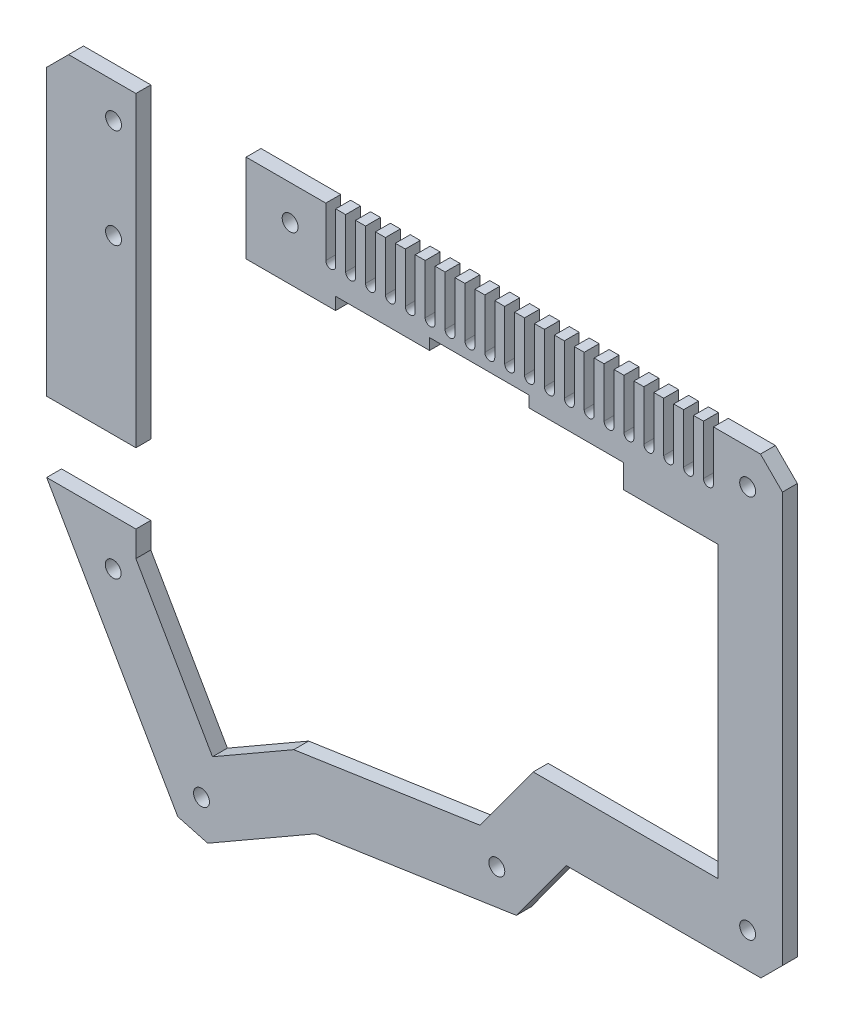
SolidWorks part; units mm, degrees
ref_plane "Plan de face" through (0, 0, 0) normal (0, 0, 1) x (1, 0, 0)
ref_plane "Plan de dessus" through (0, 0, 0) normal (0, 1, 0) x (1, 0, 0)
ref_plane "Plan de droite" through (0, 0, 0) normal (1, 0, 0) x (0, 0, -1)
sketch "Esquisse1" plane through (0, 0, 0) normal (0, 0, 1) x (1, 0, 0)
  line L0 (-117.3419, -15.4198) -> (-103.3409, -15.4198) construction
  line L1 (-103.3409, -15.4198) -> (-103.3409, -29.4208) construction
  line L2 (-103.3409, -29.4208) -> (-117.3419, -29.4208) construction
  line L3 (-117.3419, -29.4208) -> (-117.3419, -15.4198) construction
  line L4 (-98.3406, -27.0457) -> (-98.3406, -13.0447) construction
  line L5 (-98.3406, -13.0447) -> (-84.3396, -13.0447) construction
  line L6 (-84.3396, -13.0447) -> (-84.3396, -27.0457) construction
  line L7 (-84.3396, -27.0457) -> (-98.3406, -27.0457) construction
  line L8 (-79.3392, -24.6705) -> (-79.3392, -10.6695) construction
  line L9 (-79.3392, -10.6695) -> (-65.3382, -10.6695) construction
  line L10 (-65.3382, -10.6695) -> (-65.3382, -24.6705) construction
  line L11 (-65.3382, -24.6705) -> (-79.3392, -24.6705) construction
  line L12 (-60.3379, -27.0457) -> (-60.3379, -13.0447) construction
  line L13 (-60.3379, -13.0447) -> (-46.3369, -13.0447) construction
  line L14 (-46.3369, -13.0447) -> (-46.3369, -27.0457) construction
  line L15 (-46.3369, -27.0457) -> (-60.3379, -27.0457) construction
  line L16 (-41.3365, -31.796) -> (-41.3365, -17.795) construction
  line L17 (-41.3365, -17.795) -> (-27.3355, -17.795) construction
  line L18 (-27.3355, -17.795) -> (-27.3355, -31.796) construction
  line L19 (-27.3355, -31.796) -> (-41.3365, -31.796) construction
  line L20 (-22.3347, -31.796) -> (-22.3347, -17.795) construction
  line L21 (-22.3347, -17.795) -> (-8.3337, -17.795) construction
  line L22 (-8.3337, -17.795) -> (-8.3337, -31.796) construction
  line L23 (-8.3337, -31.796) -> (-22.3347, -31.796) construction
  line L24 (-117.3419, -34.4212) -> (-103.3409, -34.4212) construction
  line L25 (-103.3409, -34.4212) -> (-103.3409, -48.4222) construction
  line L26 (-103.3409, -48.4222) -> (-117.3419, -48.4222) construction
  line L27 (-117.3419, -48.4222) -> (-117.3419, -34.4212) construction
  line L28 (-98.3406, -32.046) -> (-84.3396, -32.046) construction
  line L29 (-84.3396, -32.046) -> (-84.3396, -46.047) construction
  line L30 (-84.3396, -46.047) -> (-98.3406, -46.047) construction
  line L31 (-98.3406, -46.047) -> (-98.3406, -32.046) construction
  line L32 (-79.3392, -29.6709) -> (-65.3382, -29.6709) construction
  line L33 (-65.3382, -29.6709) -> (-65.3382, -43.6718) construction
  line L34 (-65.3382, -43.6718) -> (-79.3392, -43.6718) construction
  line L35 (-79.3392, -43.6718) -> (-79.3392, -29.6709) construction
  line L36 (-60.3379, -32.046) -> (-46.3369, -32.046) construction
  line L37 (-46.3369, -32.046) -> (-46.3369, -46.047) construction
  line L38 (-46.3369, -46.047) -> (-60.3379, -46.047) construction
  line L39 (-60.3379, -46.047) -> (-60.3379, -32.046) construction
  line L40 (-41.3365, -36.7964) -> (-27.3355, -36.7964) construction
  line L41 (-27.3355, -36.7964) -> (-27.3355, -50.7973) construction
  line L42 (-27.3355, -50.7973) -> (-41.3365, -50.7973) construction
  line L43 (-41.3365, -50.7973) -> (-41.3365, -36.7964) construction
  line L44 (-22.3347, -36.7964) -> (-8.3337, -36.7964) construction
  line L45 (-8.3337, -36.7964) -> (-8.3337, -50.7973) construction
  line L46 (-8.3337, -50.7973) -> (-22.3347, -50.7973) construction
  line L47 (-22.3347, -50.7973) -> (-22.3347, -36.7964) construction
  line L48 (-22.3347, -55.7977) -> (-8.3337, -55.7977) construction
  line L49 (-8.3337, -55.7977) -> (-8.3337, -69.7987) construction
  line L50 (-8.3337, -69.7987) -> (-22.3347, -69.7987) construction
  line L51 (-22.3347, -69.7987) -> (-22.3347, -55.7977) construction
  line L52 (-41.3365, -55.7977) -> (-27.3355, -55.7977) construction
  line L53 (-27.3355, -55.7977) -> (-27.3355, -69.7987) construction
  line L54 (-27.3355, -69.7987) -> (-41.3365, -69.7987) construction
  line L55 (-41.3365, -69.7987) -> (-41.3365, -55.7977) construction
  line L56 (-60.3379, -51.0474) -> (-46.3369, -51.0474) construction
  line L57 (-46.3369, -51.0474) -> (-46.3369, -65.0484) construction
  line L58 (-46.3369, -65.0484) -> (-60.3379, -65.0484) construction
  line L59 (-60.3379, -65.0484) -> (-60.3379, -51.0474) construction
  line L60 (-79.3392, -48.6722) -> (-65.3382, -48.6722) construction
  line L61 (-65.3382, -48.6722) -> (-65.3382, -62.6732) construction
  line L62 (-65.3382, -62.6732) -> (-79.3392, -62.6732) construction
  line L63 (-79.3392, -62.6732) -> (-79.3392, -48.6722) construction
  line L64 (-98.3406, -51.0474) -> (-84.3396, -51.0474) construction
  line L65 (-84.3396, -51.0474) -> (-84.3396, -65.0484) construction
  line L66 (-84.3396, -65.0484) -> (-98.3406, -65.0484) construction
  line L67 (-98.3406, -65.0484) -> (-98.3406, -51.0474) construction
  line L68 (-117.3419, -53.4225) -> (-103.3409, -53.4225) construction
  line L69 (-103.3409, -53.4225) -> (-103.3409, -67.4235) construction
  line L70 (-103.3409, -67.4235) -> (-117.3419, -67.4235) construction
  line L71 (-117.3419, -67.4235) -> (-117.3419, -53.4225) construction
  line L72 (-88.8399, -70.6738) -> (-74.8389, -70.6738) construction
  line L73 (-74.8389, -70.6738) -> (-74.8389, -84.6747) construction
  line L74 (-74.8389, -84.6747) -> (-88.8399, -84.6747) construction
  line L75 (-88.8399, -84.6747) -> (-88.8399, -70.6738) construction
  line L76 (-111.4175, -75.4665) -> (-97.8899, -71.8565) construction
  line L77 (-97.8899, -71.8565) -> (-94.28, -85.3841) construction
  line L78 (-94.28, -85.3841) -> (-107.8075, -88.9941) construction
  line L79 (-107.8075, -88.9941) -> (-111.4175, -75.4665) construction
  line L80 (-134.6581, -81.5997) -> (-122.5281, -74.6075) construction
  line L81 (-122.5281, -74.6075) -> (-115.5359, -86.7375) construction
  line L82 (-115.5359, -86.7375) -> (-127.6659, -93.7297) construction
  line L83 (-127.6659, -93.7297) -> (-134.6581, -81.5997) construction
  line L86 (-6.4297, -71.9336) -> (-62.0853, -71.9336) construction
  line L89 (-72.824, -86.6446) -> (-62.0853, -71.9336) construction
  line L96 (-109.7697, -91.4639) -> (-73.0906, -86.6918) construction
  line L97 (-124.664, -99.8297) -> (-110.3971, -91.5881) construction
  line L98 (-139.9408, -76.5013) -> (-126.7151, -99.4281) construction
  line L99 (-119.8527, -15.5421) -> (-139.6028, -15.5421) construction
  line L100 (-100.8528, -13.2921) -> (-118.8527, -13.2921) construction
  line L101 (-63.8455, -8.5421) -> (-80.8528, -8.5421) construction
  line L102 (-44.8455, -10.792) -> (-62.8485, -10.792) construction
  line L103 (-25.8456, -15.5421) -> (-43.8486, -15.5421) construction
  line L104 (-6.8456, -15.5421) -> (-23.8529, -15.5421) construction
  line L105 (-6.2741, -71.3672) -> (-6.2741, -16.1136) construction
  line L106 (-23.8529, -71.9423) -> (-6.8456, -71.9423) construction
  line L107 (-61.8455, -71.9423) -> (-25.8456, -71.9423) construction
  line L108 (-72.6738, -86.4911) -> (-62.1363, -72.0583) construction
  line L109 (-140.1743, -16.1136) -> (-140.1743, -75.5958) construction
  line L110 (-134.3462, 1.5705) -> (-134.3466, -55.7217) construction
  line L111 (-134.3466, -55.7217) -> (-160.479, -70.8411) construction
  line L112 (-160.479, -70.8411) -> (-133.7613, -117.344) construction
  line L113 (-126.937, -119.1852) -> (-105.0783, -106.604) construction
  line L114 (-105.0783, -106.604) -> (-64.4097, -100.5586) construction
  line L115 (-64.4097, -100.5586) -> (-54.4636, -86.9336) construction
  line L116 (3.6609, -86.9336) -> (-54.4636, -86.9336) construction
  line L117 (-10.4297, -82.0242) -> (-10.4297, 1.315) construction
  line L129 (8.5703, -86.9336) -> (8.5703, -0.6796) construction
  line L130 (-48.4337, 6.3182) -> (-96.435, 6.3209) construction
  line L131 (-115.3458, 1.5705) -> (-134.3462, 1.5705) construction
  line L132 (-160.479, -3.4295) -> (-160.479, -70.8411) construction
  line L134 (-119.3463, 1.5705) -> (-119.3464, -12.4295)
  line L135 (-119.3466, -64.3728) -> (-135.695, -73.8315) construction
  line L136 (-140.0228, -76.3355) -> (-140.0228, -76.3321)
  line L138 (-160.479, -70.8411) -> (-131.2704, -121.6794) construction
  line L139 (-131.2704, -121.6794) -> (-105.0783, -106.604) construction
  line L140 (-133.7613, -117.344) -> (-126.937, -119.1852) construction
  line L142 (-10.4297, 1.315) -> (-15.4297, 6.3153) construction
  line L143 (8.5703, -86.9336) -> (-54.4636, -86.9336) construction
  line L144 (-10.4297, -82.0242) -> (-15.3391, -86.9336) construction
  line L150 (-140.0228, 1.5705) -> (-140.0228, 6.3209) construction
  line L151 (-140.0228, 6.3209) -> (-155.479, 6.3209) construction
  line L152 (-160.479, 1.3209) -> (-160.479, -3.4295) construction
  line L153 (-155.479, 6.3209) -> (-160.479, 1.3209) construction
  line L154 (-103.4315, 5.3209) -> (-118.3463, 5.3209) construction
  line L155 (-146.0924, -79.8227) -> (-128.3223, -110.752) construction
  line L156 (-128.3223, -110.752) -> (-107.7547, -98.9139) construction
  line L157 (-140.0228, -78.3428) -> (-126.1111, -102.5565)
  line L158 (-126.1111, -102.5565) -> (-109.762, -93.1464)
  line L159 (-109.762, -93.1464) -> (-72.2631, -87.5722)
  line L160 (-72.2631, -87.5722) -> (-61.5772, -72.9336)
  line L161 (-10.4297, -72.9336) -> (-11.4297, -72.9336)
  line L162 (-24.4297, -72.9336) -> (-24.4297, -14.6796)
  line L164 (-43.4324, -14.6796) -> (-43.4324, -9.9293)
  line L165 (-43.4324, -9.9293) -> (-62.4337, -9.9293)
  line L166 (-62.4337, -9.9293) -> (-62.4337, -7.681)
  line L167 (-62.4337, -7.681) -> (-82.435, -7.6799)
  line L168 (-82.435, -7.6799) -> (-82.435, -9.9293)
  line L169 (-82.435, -9.9293) -> (-101.3458, -9.9293)
  line L170 (-101.3458, -9.9293) -> (-101.3458, -12.4295)
  line L171 (-101.3458, -12.4295) -> (-119.3464, -12.4295)
  line L172 (-120.3463, -12.4295) -> (-120.3466, -64.3728) construction
  line L173 (-119.8474, -63.5072) -> (-140.5236, -75.4699) construction
  line L174 (-107.7547, -98.9139) -> (-68.8973, -93.1378) construction
  line L175 (-68.8973, -93.1378) -> (-58.5285, -78.9336) construction
  line L176 (0.5703, -78.9336) -> (-58.5285, -78.9336) construction
  line L177 (-18.4297, -78.9336) -> (-18.4297, -1.6845) construction
  line L178 (-15.8495, 5.3209) -> (-119.3463, 5.3209)
  line L179 (0.5703, -78.9336) -> (0.5703, -14.6796) construction
  line L180 (-146.0228, -76.3355) -> (-146.0228, 1.5705) construction
  line L181 (-140.0228, -76.3355) -> (-140.0228, 1.5705) construction
  line L182 (-135.695, -73.8315) -> (-140.0228, -71.3355) construction
  line L186 (-118.3463, 5.3209) -> (-118.3463, 1.5705) construction
  line L187 (-118.3463, 1.5705) -> (-118.3466, -64.9495) construction
  line L188 (-118.3466, -64.9495) -> (-135.6942, -74.9864) construction
  line L189 (-135.6942, -74.9864) -> (-141.0228, -71.9131) construction
  line L190 (-141.0228, -71.9131) -> (-141.0228, 1.5705) construction
  line L191 (-141.0228, 1.5705) -> (-141.0228, 5.3209) construction
  line L192 (-141.5228, 5.3209) -> (-155.0648, 5.3209)
  line L193 (-155.0648, 5.3209) -> (-159.479, 0.9066)
  line L194 (-159.479, 0.9066) -> (-159.479, -3.4295)
  line L195 (-159.479, -3.4295) -> (-159.479, -70.5743)
  line L196 (-159.479, -70.5743) -> (-133.1007, -116.4865)
  line L197 (-133.1007, -116.4865) -> (-127.0766, -118.1118)
  line L198 (-127.0766, -118.1118) -> (-105.4129, -105.6427)
  line L199 (-105.4129, -105.6427) -> (-64.9706, -99.631)
  line L200 (-64.9706, -99.631) -> (-54.9717, -85.9336)
  line L202 (-11.4297, -81.61) -> (-15.7533, -85.9336)
  line L203 (-11.4297, -81.61) -> (-11.4297, 0.9008)
  line L204 (-11.4297, 0.9008) -> (-15.8495, 5.3209)
  line L206 (-140.0228, -76.3321) -> (-119.3466, -64.3728) construction
  line L207 (-140.0228, -71.3355) -> (-140.0228, 1.5705) construction
  line L208 (-119.3463, 5.3209) -> (-119.3463, 1.5705)
  line L209 (-140.8899, -76.8336) -> (-126.1111, -102.5565) construction
  line L210 (-119.3463, 1.5705) -> (-119.3466, -64.3728) construction
  line L211 (-101.3458, -12.4295) -> (-120.3463, -12.4295) construction
  line L212 (-119.3463, 6.3209) -> (-119.3463, 1.5705) construction
  line L217 (-6.4297, -71.9336) -> (-6.4297, -15.6796) construction
  line L220 (-6.4297, -15.6796) -> (-44.4324, -15.6796) construction
  line L221 (-44.4324, -15.6796) -> (-44.4324, -10.9293) construction
  line L222 (-44.4324, -10.9293) -> (-63.4337, -10.9293) construction
  line L223 (-63.4337, -10.9293) -> (-63.4337, -8.681) construction
  line L224 (-63.4337, -8.681) -> (-81.435, -8.68) construction
  line L225 (-81.435, -8.68) -> (-81.435, -10.9293) construction
  line L226 (-81.435, -10.9293) -> (-100.3458, -10.9293) construction
  line L227 (-100.3458, -10.9293) -> (-100.3458, -13.4295) construction
  line L228 (-100.3458, -13.4295) -> (-119.3463, -13.4295) construction
  line L231 (-119.3463, -13.4295) -> (-119.3466, -64.3728) construction
  line L232 (-119.3466, -64.3728) -> (-140.0228, -76.3355) construction
  line L233 (-140.0228, -76.3355) -> (-125.7426, -101.1906) construction
  line L234 (-125.7426, -101.1906) -> (-110.0965, -92.1851) construction
  line L235 (-110.0965, -92.1851) -> (-72.824, -86.6446) construction
  line L237 (7.5703, 0.9008) -> (3.1561, 5.3153) construction
  line L238 (-140.0228, -76.3355) -> (-140.8899, -76.8336) construction
  line L241 (-140.8899, -76.8336) -> (-140.0228, -78.3428)
  line L244 (-140.521, -75.4684) -> (-140.5223, -75.4691)
  line L247 (-141.5228, -75.732) -> (-140.8899, -76.8336)
  line L253 (-140.0228, -75.1802) -> (-140.0228, 5.3209) construction
  line L256 (-146.0228, -1.6779) -> (-146.0228, -21.6805) construction
  line L259 (-141.5228, -75.1802) -> (-141.5228, 5.3209)
  line L262 (-141.5228, -75.1802) -> (-141.5228, -75.732)
  line L265 (-141.0228, 5.3209) -> (-155.0648, 5.3209) construction
  line L268 (-5.4297, -72.9336) -> (-5.4297, -14.6796) construction
  line L271 (-140.521, -75.4684) -> (-141.3881, -75.9666) construction
  line L274 (8.5703, -82.0242) -> (3.6609, -86.9336) construction
  line L277 (7.5703, -81.61) -> (3.2467, -85.9336) construction
  line L280 (8.5703, -82.0242) -> (8.5703, 1.315) construction
  line L283 (7.5703, -81.61) -> (7.5703, 0.9008) construction
  line L286 (8.5703, 1.315) -> (3.5703, 6.3153) construction
  line L289 (-24.4297, -14.6796) -> (-43.4324, -14.6796)
  line L292 (-24.4297, -72.9336) -> (-61.5772, -72.9336)
  line L295 (-5.4297, -14.6796) -> (-43.4324, -14.6796) construction
  line L298 (-15.7533, -85.9336) -> (-54.9717, -85.9336)
  line L301 (-5.4297, -72.9336) -> (-61.5772, -72.9336) construction
  line L307 (3.2467, -85.9336) -> (-54.9717, -85.9336) construction
  line L321 (3.1561, 5.3153) -> (-96.435, 5.3209) construction
  line L328 (-48.4337, 4.0707) -> (-48.4337, 6.3182) construction
  line L329 (-29.4324, 4.0707) -> (-48.4337, 4.0707) construction
  line L330 (-29.4324, -0.6796) -> (-29.4324, 4.0707) construction
  line L331 (8.5703, -0.6796) -> (-29.4324, -0.6796) construction
  line L332 (-115.3458, 4.0707) -> (-115.3458, 1.5705) construction
  line L333 (-96.435, 4.0707) -> (-115.3458, 4.0707) construction
  line L334 (-96.435, 6.3209) -> (-96.435, 4.0707) construction
  line L368 (-103.4315, 5.3209) -> (-96.435, 5.3209) construction
  line L386 (3.5703, 6.3153) -> (-96.435, 6.3209) construction
  line L438 (-103.4315, 6.3209) -> (-96.435, 6.3209) construction
  line L439 (-103.4315, 6.3209) -> (-119.3463, 6.3209) construction
  circle A2 centre (-18.4297, -1.6845) radius 1.6
  circle A3 centre (-18.4297, -1.6845) radius 3 construction
  circle A4 centre (-110.4876, -1.6784) radius 1.6
  circle A5 centre (-18.4297, -78.9336) radius 1.6
  circle A6 centre (-68.8973, -93.1378) radius 1.6
  circle A7 centre (-128.3223, -110.752) radius 1.6
  circle A8 centre (-146.0924, -79.8227) radius 1.6
  circle A9 centre (-146.0228, -1.6779) radius 1.6
  circle A10 centre (-110.4876, -1.6784) radius 3 construction
  circle A11 centre (-146.0228, -1.6779) radius 3 construction
  circle A12 centre (-146.0924, -79.8227) radius 3 construction
  circle A13 centre (-128.3223, -110.752) radius 3 construction
  circle A14 centre (-68.8973, -93.1378) radius 3 construction
  circle A15 centre (-18.4297, -78.9336) radius 3 construction
  circle A16 centre (-146.0228, -21.6805) radius 1.6
  point P138 (-160.479, 1.5705)
  point P139 (-10.4297, 6.315)
  point P150 (-160.479, 6.3209)
  dimension "D3" = 3.2
  dimension "D4" = 6
  dimension "D6" = 3.2
  dimension "D7" = 3.2
  dimension "D8" = 3.2
  dimension "D9" = 3.2
  dimension "D10" = 3.2
  dimension "D15" = 3.2
  dimension "D2" = 1
  dimension "D1" = 15
  dimension "D5" = 1
  dimension "D13" = 6
  dimension "D16" = 1.5
extrude "Boss.-Extru.1" add sketch "Esquisse1" along normal blind 3
sketch "Esquisse2" plane through (0, 0, 3) normal (0, 0, 1) x (1, 0, 0)
  line L19 (-26.3155, 8.6159) -> (-26.3155, -4.6791) construction
  line L20 (-25.3155, 8.6159) -> (-25.3155, -4.6791)
  line L21 (-27.3155, 8.6159) -> (-27.3155, -4.6791)
  line L22 (-30.3155, 8.6159) -> (-30.3155, -4.6791) construction
  line L23 (-29.3155, 8.6159) -> (-29.3155, -4.6791)
  line L24 (-31.3155, 8.6159) -> (-31.3155, -4.6791)
  line L25 (-34.3155, 8.6159) -> (-34.3155, -4.6791) construction
  line L26 (-33.3155, 8.6159) -> (-33.3155, -4.6791)
  line L27 (-35.3155, 8.6159) -> (-35.3155, -4.6791)
  line L28 (-38.3155, 8.6159) -> (-38.3155, -4.6791) construction
  line L29 (-37.3155, 8.6159) -> (-37.3155, -4.6791)
  line L30 (-39.3155, 8.6159) -> (-39.3155, -4.6791)
  line L31 (-42.3155, 8.6159) -> (-42.3155, -4.6791) construction
  line L32 (-41.3155, 8.6159) -> (-41.3155, -4.6791)
  line L33 (-43.3155, 8.6159) -> (-43.3155, -4.6791)
  line L34 (-46.3155, 8.6159) -> (-46.3155, -4.6791) construction
  line L35 (-45.3155, 8.6159) -> (-45.3155, -4.6791)
  line L36 (-47.3155, 8.6159) -> (-47.3155, -4.6791)
  line L37 (-50.3155, 8.6159) -> (-50.3155, -4.6791) construction
  line L38 (-49.3155, 8.6159) -> (-49.3155, -4.6791)
  line L39 (-51.3155, 8.6159) -> (-51.3155, -4.6791)
  line L40 (-54.3155, 8.6159) -> (-54.3155, -4.6791) construction
  line L41 (-53.3155, 8.6159) -> (-53.3155, -4.6791)
  line L42 (-55.3155, 8.6159) -> (-55.3155, -4.6791)
  line L43 (-58.3155, 8.6159) -> (-58.3155, -4.6791) construction
  line L44 (-57.3155, 8.6159) -> (-57.3155, -4.6791)
  line L45 (-59.3155, 8.6159) -> (-59.3155, -4.6791)
  line L46 (-62.3155, 8.6159) -> (-62.3155, -4.6791) construction
  line L47 (-61.3155, 8.6159) -> (-61.3155, -4.6791)
  line L48 (-63.3155, 8.6159) -> (-63.3155, -4.6791)
  line L49 (-66.3155, 8.6159) -> (-66.3155, -4.6791) construction
  line L50 (-65.3155, 8.6159) -> (-65.3155, -4.6791)
  line L51 (-67.3155, 8.6159) -> (-67.3155, -4.6791)
  line L52 (-70.3155, 8.6159) -> (-70.3155, -4.6791) construction
  line L53 (-69.3155, 8.6159) -> (-69.3155, -4.6791)
  line L54 (-71.3155, 8.6159) -> (-71.3155, -4.6791)
  line L55 (-74.3155, 8.6159) -> (-74.3155, -4.6791) construction
  line L56 (-73.3155, 8.6159) -> (-73.3155, -4.6791)
  line L57 (-75.3155, 8.6159) -> (-75.3155, -4.6791)
  line L58 (-78.3155, 8.6159) -> (-78.3155, -4.6791) construction
  line L59 (-77.3155, 8.6159) -> (-77.3155, -4.6791)
  line L60 (-79.3155, 8.6159) -> (-79.3155, -4.6791)
  line L61 (-82.3155, 8.6159) -> (-82.3155, -4.6791) construction
  line L62 (-81.3155, 8.6159) -> (-81.3155, -4.6791)
  line L63 (-83.3155, 8.6159) -> (-83.3155, -4.6791)
  line L64 (-86.3155, 8.6159) -> (-86.3155, -4.6791) construction
  line L65 (-85.3155, 8.6159) -> (-85.3155, -4.6791)
  line L66 (-87.3155, 8.6159) -> (-87.3155, -4.6791)
  line L67 (-90.3155, 8.6159) -> (-90.3155, -4.6791) construction
  line L68 (-89.3155, 8.6159) -> (-89.3155, -4.6791)
  line L69 (-91.3155, 8.6159) -> (-91.3155, -4.6791)
  line L70 (-94.3155, 8.6159) -> (-94.3155, -4.6791) construction
  line L71 (-93.3155, 8.6159) -> (-93.3155, -4.6791)
  line L72 (-95.3155, 8.6159) -> (-95.3155, -4.6791)
  line L73 (-98.3155, 8.6159) -> (-98.3155, -4.6791) construction
  line L74 (-97.3155, 8.6159) -> (-97.3155, -4.6791)
  line L75 (-99.3155, 8.6159) -> (-99.3155, -4.6791)
  line L76 (-102.3155, 8.6159) -> (-102.3155, -4.6791) construction
  line L77 (-101.3155, 8.6159) -> (-101.3155, -4.6791)
  line L78 (-103.3155, 8.6159) -> (-103.3155, -4.6791)
  arc A10 (-25.3155, 8.6159) -> (-27.3155, 8.6159) centre (-26.3155, 8.6159) ccw
  arc A11 (-27.3155, -4.6791) -> (-25.3155, -4.6791) centre (-26.3155, -4.6791) ccw
  arc A12 (-29.3155, 8.6159) -> (-31.3155, 8.6159) centre (-30.3155, 8.6159) ccw
  arc A13 (-31.3155, -4.6791) -> (-29.3155, -4.6791) centre (-30.3155, -4.6791) ccw
  arc A14 (-33.3155, 8.6159) -> (-35.3155, 8.6159) centre (-34.3155, 8.6159) ccw
  arc A15 (-35.3155, -4.6791) -> (-33.3155, -4.6791) centre (-34.3155, -4.6791) ccw
  arc A16 (-37.3155, 8.6159) -> (-39.3155, 8.6159) centre (-38.3155, 8.6159) ccw
  arc A17 (-39.3155, -4.6791) -> (-37.3155, -4.6791) centre (-38.3155, -4.6791) ccw
  arc A18 (-41.3155, 8.6159) -> (-43.3155, 8.6159) centre (-42.3155, 8.6159) ccw
  arc A19 (-43.3155, -4.6791) -> (-41.3155, -4.6791) centre (-42.3155, -4.6791) ccw
  arc A20 (-45.3155, 8.6159) -> (-47.3155, 8.6159) centre (-46.3155, 8.6159) ccw
  arc A21 (-47.3155, -4.6791) -> (-45.3155, -4.6791) centre (-46.3155, -4.6791) ccw
  arc A22 (-49.3155, 8.6159) -> (-51.3155, 8.6159) centre (-50.3155, 8.6159) ccw
  arc A23 (-51.3155, -4.6791) -> (-49.3155, -4.6791) centre (-50.3155, -4.6791) ccw
  arc A24 (-53.3155, 8.6159) -> (-55.3155, 8.6159) centre (-54.3155, 8.6159) ccw
  arc A25 (-55.3155, -4.6791) -> (-53.3155, -4.6791) centre (-54.3155, -4.6791) ccw
  arc A26 (-57.3155, 8.6159) -> (-59.3155, 8.6159) centre (-58.3155, 8.6159) ccw
  arc A27 (-59.3155, -4.6791) -> (-57.3155, -4.6791) centre (-58.3155, -4.6791) ccw
  arc A28 (-61.3155, 8.6159) -> (-63.3155, 8.6159) centre (-62.3155, 8.6159) ccw
  arc A29 (-63.3155, -4.6791) -> (-61.3155, -4.6791) centre (-62.3155, -4.6791) ccw
  arc A30 (-65.3155, 8.6159) -> (-67.3155, 8.6159) centre (-66.3155, 8.6159) ccw
  arc A31 (-67.3155, -4.6791) -> (-65.3155, -4.6791) centre (-66.3155, -4.6791) ccw
  arc A32 (-69.3155, 8.6159) -> (-71.3155, 8.6159) centre (-70.3155, 8.6159) ccw
  arc A33 (-71.3155, -4.6791) -> (-69.3155, -4.6791) centre (-70.3155, -4.6791) ccw
  arc A34 (-73.3155, 8.6159) -> (-75.3155, 8.6159) centre (-74.3155, 8.6159) ccw
  arc A35 (-75.3155, -4.6791) -> (-73.3155, -4.6791) centre (-74.3155, -4.6791) ccw
  arc A36 (-77.3155, 8.6159) -> (-79.3155, 8.6159) centre (-78.3155, 8.6159) ccw
  arc A37 (-79.3155, -4.6791) -> (-77.3155, -4.6791) centre (-78.3155, -4.6791) ccw
  arc A38 (-81.3155, 8.6159) -> (-83.3155, 8.6159) centre (-82.3155, 8.6159) ccw
  arc A39 (-83.3155, -4.6791) -> (-81.3155, -4.6791) centre (-82.3155, -4.6791) ccw
  arc A40 (-85.3155, 8.6159) -> (-87.3155, 8.6159) centre (-86.3155, 8.6159) ccw
  arc A41 (-87.3155, -4.6791) -> (-85.3155, -4.6791) centre (-86.3155, -4.6791) ccw
  arc A42 (-89.3155, 8.6159) -> (-91.3155, 8.6159) centre (-90.3155, 8.6159) ccw
  arc A43 (-91.3155, -4.6791) -> (-89.3155, -4.6791) centre (-90.3155, -4.6791) ccw
  arc A44 (-93.3155, 8.6159) -> (-95.3155, 8.6159) centre (-94.3155, 8.6159) ccw
  arc A45 (-95.3155, -4.6791) -> (-93.3155, -4.6791) centre (-94.3155, -4.6791) ccw
  arc A46 (-97.3155, 8.6159) -> (-99.3155, 8.6159) centre (-98.3155, 8.6159) ccw
  arc A47 (-99.3155, -4.6791) -> (-97.3155, -4.6791) centre (-98.3155, -4.6791) ccw
  arc A48 (-101.3155, 8.6159) -> (-103.3155, 8.6159) centre (-102.3155, 8.6159) ccw
  arc A49 (-103.3155, -4.6791) -> (-101.3155, -4.6791) centre (-102.3155, -4.6791) ccw
  point P45 (-26.3155, 1.9684)
  point P52 (-30.3155, 1.9684)
  point P59 (-34.3155, 1.9684)
  point P66 (-38.3155, 1.9684)
  point P73 (-42.3155, 1.9684)
  point P80 (-46.3155, 1.9684)
  point P87 (-50.3155, 1.9684)
  point P94 (-54.3155, 1.9684)
  point P101 (-58.3155, 1.9684)
  point P108 (-62.3155, 1.9684)
  point P115 (-66.3155, 1.9684)
  point P122 (-70.3155, 1.9684)
  point P129 (-74.3155, 1.9684)
  point P136 (-78.3155, 1.9684)
  point P143 (-82.3155, 1.9684)
  point P150 (-86.3155, 1.9684)
  point P157 (-90.3155, 1.9684)
  point P164 (-94.3155, 1.9684)
  point P171 (-98.3155, 1.9684)
  point P178 (-102.3155, 1.9684)
extrude "Enlèv. mat.-Extru.1" cut sketch "Esquisse2" against normal blind 10
sketch "Esquisse3" plane through (0, 0, 3) normal (0, 0, 1) x (1, 0, 0)
  line L0 (-159.479, -70.5743) -> (-140.0228, -70.5743)
  line L1 (-140.0228, -75.1802) -> (-140.0228, 5.3209) construction
  line L2 (-117.3419, -53.4225) -> (-140.0228, -53.4225) construction
  line L3 (-140.0228, -53.4225) -> (-140.0228, -56.4239) construction
  line L4 (-140.0228, -70.5743) -> (-140.0228, -56.4239)
  line L5 (-140.0228, -56.4239) -> (-159.479, -56.4239)
  line L6 (-159.479, -3.4295) -> (-159.479, -70.5743) construction
  line L7 (-159.479, -56.4239) -> (-159.479, -70.5743)
extrude "Enlèv. mat.-Extru.2" cut sketch "Esquisse3" against normal blind 10
sketch "Esquisse4" plane through (0, 0, 3) normal (0, 0, 1) x (1, 0, 0)
  line L5 (-159.479, -56.4239) -> (-141.5228, -56.4239)
  line L6 (-141.5228, -56.4239) -> (-141.5228, 5.3209)
  line L7 (-141.5228, 5.3209) -> (-155.0648, 5.3209)
  line L8 (-155.0648, 5.3209) -> (-159.479, 0.9066)
  line L9 (-159.479, 0.9066) -> (-159.479, -56.4239)
  line L10 (-159.479, -56.4239) -> (-141.5228, -56.4239)
  line L11 (-141.5228, -56.4239) -> (-141.5228, 5.3209)
  line L12 (-141.5228, 5.3209) -> (-155.0648, 5.3209)
  line L13 (-155.0648, 5.3209) -> (-159.479, 0.9066)
  line L14 (-159.479, 0.9066) -> (-159.479, -56.4239)
  line L104 (-141.5228, -70.5743) -> (-159.479, -70.5743)
  line L105 (-159.479, -70.5743) -> (-133.1007, -116.4865)
  line L106 (-133.1007, -116.4865) -> (-127.0766, -118.1118)
  line L107 (-127.0766, -118.1118) -> (-105.4129, -105.6427)
  line L108 (-105.4129, -105.6427) -> (-64.9706, -99.631)
  line L109 (-64.9706, -99.631) -> (-54.9717, -85.9336)
  line L110 (-54.9717, -85.9336) -> (-15.7533, -85.9336)
  line L111 (-15.7533, -85.9336) -> (-11.4297, -81.61)
  line L112 (-11.4297, -81.61) -> (-11.4297, 0.9008)
  line L113 (-11.4297, 0.9008) -> (-15.8495, 5.3209)
  line L114 (-15.8495, 5.3209) -> (-25.3155, 5.3209)
  line L115 (-54.9717, -85.9336) -> (-15.7533, -85.9336)
  line L130 (-25.3155, 5.3209) -> (-25.3155, -4.6791)
  line L131 (-27.3155, -4.6791) -> (-27.3155, 5.3209)
  line L132 (-27.3155, 5.3209) -> (-29.3155, 5.3209)
  line L133 (-29.3155, 5.3209) -> (-29.3155, -4.6791)
  line L134 (-31.3155, -4.6791) -> (-31.3155, 5.3209)
  line L135 (-31.3155, 5.3209) -> (-33.3155, 5.3209)
  line L136 (-33.3155, 5.3209) -> (-33.3155, -4.6791)
  line L137 (-35.3155, -4.6791) -> (-35.3155, 5.3209)
  line L138 (-35.3155, 5.3209) -> (-37.3155, 5.3209)
  line L139 (-37.3155, 5.3209) -> (-37.3155, -4.6791)
  line L140 (-39.3155, -4.6791) -> (-39.3155, 5.3209)
  line L141 (-39.3155, 5.3209) -> (-41.3155, 5.3209)
  line L142 (-41.3155, 5.3209) -> (-41.3155, -4.6791)
  line L143 (-43.3155, -4.6791) -> (-43.3155, 5.3209)
  line L144 (-43.3155, 5.3209) -> (-45.3155, 5.3209)
  line L145 (-45.3155, 5.3209) -> (-45.3155, -4.6791)
  line L146 (-47.3155, -4.6791) -> (-47.3155, 5.3209)
  line L147 (-47.3155, 5.3209) -> (-49.3155, 5.3209)
  line L148 (-49.3155, 5.3209) -> (-49.3155, -4.6791)
  line L149 (-51.3155, -4.6791) -> (-51.3155, 5.3209)
  line L150 (-51.3155, 5.3209) -> (-53.3155, 5.3209)
  line L151 (-53.3155, 5.3209) -> (-53.3155, -4.6791)
  line L152 (-55.3155, -4.6791) -> (-55.3155, 5.3209)
  line L153 (-55.3155, 5.3209) -> (-57.3155, 5.3209)
  line L154 (-57.3155, 5.3209) -> (-57.3155, -4.6791)
  line L155 (-59.3155, -4.6791) -> (-59.3155, 5.3209)
  line L156 (-59.3155, 5.3209) -> (-61.3155, 5.3209)
  line L157 (-61.3155, 5.3209) -> (-61.3155, -4.6791)
  line L158 (-63.3155, -4.6791) -> (-63.3155, 5.3209)
  line L159 (-63.3155, 5.3209) -> (-65.3155, 5.3209)
  line L160 (-65.3155, 5.3209) -> (-65.3155, -4.6791)
  line L161 (-67.3155, -4.6791) -> (-67.3155, 5.3209)
  line L162 (-67.3155, 5.3209) -> (-69.3155, 5.3209)
  line L163 (-69.3155, 5.3209) -> (-69.3155, -4.6791)
  line L164 (-71.3155, -4.6791) -> (-71.3155, 5.3209)
  line L165 (-71.3155, 5.3209) -> (-73.3155, 5.3209)
  line L166 (-73.3155, 5.3209) -> (-73.3155, -4.6791)
  line L167 (-75.3155, -4.6791) -> (-75.3155, 5.3209)
  line L168 (-75.3155, 5.3209) -> (-77.3155, 5.3209)
  line L169 (-77.3155, 5.3209) -> (-77.3155, -4.6791)
  line L170 (-79.3155, -4.6791) -> (-79.3155, 5.3209)
  line L171 (-79.3155, 5.3209) -> (-81.3155, 5.3209)
  line L172 (-81.3155, 5.3209) -> (-81.3155, -4.6791)
  line L173 (-83.3155, -4.6791) -> (-83.3155, 5.3209)
  line L174 (-83.3155, 5.3209) -> (-85.3155, 5.3209)
  line L175 (-85.3155, 5.3209) -> (-85.3155, -4.6791)
  line L176 (-87.3155, -4.6791) -> (-87.3155, 5.3209)
  line L177 (-87.3155, 5.3209) -> (-89.3155, 5.3209)
  line L178 (-89.3155, 5.3209) -> (-89.3155, -4.6791)
  line L179 (-91.3155, -4.6791) -> (-91.3155, 5.3209)
  line L180 (-91.3155, 5.3209) -> (-93.3155, 5.3209)
  line L181 (-93.3155, 5.3209) -> (-93.3155, -4.6791)
  line L182 (-95.3155, -4.6791) -> (-95.3155, 5.3209)
  line L183 (-95.3155, 5.3209) -> (-97.3155, 5.3209)
  line L184 (-97.3155, 5.3209) -> (-97.3155, -4.6791)
  line L185 (-99.3155, -4.6791) -> (-99.3155, 5.3209)
  line L186 (-99.3155, 5.3209) -> (-101.3155, 5.3209)
  line L187 (-101.3155, 5.3209) -> (-101.3155, -4.6791)
  line L188 (-103.3155, -4.6791) -> (-103.3155, 5.3209)
  line L189 (-103.3155, 5.3209) -> (-119.3463, 5.3209)
  line L190 (-119.3463, 5.3209) -> (-119.3463, 1.5705)
  line L191 (-119.3463, 1.5705) -> (-119.3464, -12.4295)
  line L192 (-119.3464, -12.4295) -> (-101.3458, -12.4295)
  line L193 (-101.3458, -12.4295) -> (-101.3458, -9.9293)
  line L194 (-101.3458, -9.9293) -> (-82.435, -9.9293)
  line L195 (-82.435, -9.9293) -> (-82.435, -7.6799)
  line L196 (-82.435, -7.6799) -> (-62.4337, -7.681)
  line L197 (-62.4337, -7.681) -> (-62.4337, -9.9293)
  line L198 (-62.4337, -9.9293) -> (-43.4324, -9.9293)
  line L199 (-43.4324, -9.9293) -> (-43.4324, -14.6796)
  line L200 (-43.4324, -14.6796) -> (-24.4297, -14.6796)
  line L201 (-24.4297, -14.6796) -> (-24.4297, -72.9336)
  line L202 (-43.4324, -14.6796) -> (-24.4297, -14.6796)
  line L203 (-61.5772, -72.9336) -> (-72.2631, -87.5722)
  line L204 (-72.2631, -87.5722) -> (-109.762, -93.1464)
  line L205 (-109.762, -93.1464) -> (-126.1111, -102.5565)
  line L206 (-126.1111, -102.5565) -> (-141.5228, -75.732)
  line L207 (-141.5228, -75.732) -> (-141.5228, -70.5743)
  line L208 (-141.5228, -70.5743) -> (-159.479, -70.5743)
  line L209 (-159.479, -70.5743) -> (-133.1007, -116.4865)
  line L210 (-133.1007, -116.4865) -> (-127.0766, -118.1118)
  line L211 (-127.0766, -118.1118) -> (-105.4129, -105.6427)
  line L212 (-105.4129, -105.6427) -> (-64.9706, -99.631)
  line L213 (-64.9706, -99.631) -> (-54.9717, -85.9336)
  line L215 (-15.7533, -85.9336) -> (-11.4297, -81.61)
  line L216 (-11.4297, -81.61) -> (-11.4297, 0.9008)
  line L217 (-11.4297, 0.9008) -> (-15.8495, 5.3209)
  line L218 (-15.8495, 5.3209) -> (-25.3155, 5.3209)
  line L234 (-25.3155, 5.3209) -> (-25.3155, -4.6791)
  line L235 (-27.3155, -4.6791) -> (-27.3155, 5.3209)
  line L236 (-27.3155, 5.3209) -> (-29.3155, 5.3209)
  line L237 (-29.3155, 5.3209) -> (-29.3155, -4.6791)
  line L238 (-31.3155, -4.6791) -> (-31.3155, 5.3209)
  line L239 (-31.3155, 5.3209) -> (-33.3155, 5.3209)
  line L240 (-33.3155, 5.3209) -> (-33.3155, -4.6791)
  line L241 (-35.3155, -4.6791) -> (-35.3155, 5.3209)
  line L242 (-35.3155, 5.3209) -> (-37.3155, 5.3209)
  line L243 (-37.3155, 5.3209) -> (-37.3155, -4.6791)
  line L244 (-39.3155, -4.6791) -> (-39.3155, 5.3209)
  line L245 (-39.3155, 5.3209) -> (-41.3155, 5.3209)
  line L246 (-41.3155, 5.3209) -> (-41.3155, -4.6791)
  line L247 (-43.3155, -4.6791) -> (-43.3155, 5.3209)
  line L248 (-43.3155, 5.3209) -> (-45.3155, 5.3209)
  line L249 (-45.3155, 5.3209) -> (-45.3155, -4.6791)
  line L250 (-47.3155, -4.6791) -> (-47.3155, 5.3209)
  line L251 (-47.3155, 5.3209) -> (-49.3155, 5.3209)
  line L252 (-49.3155, 5.3209) -> (-49.3155, -4.6791)
  line L253 (-51.3155, -4.6791) -> (-51.3155, 5.3209)
  line L254 (-51.3155, 5.3209) -> (-53.3155, 5.3209)
  line L255 (-53.3155, 5.3209) -> (-53.3155, -4.6791)
  line L256 (-55.3155, -4.6791) -> (-55.3155, 5.3209)
  line L257 (-55.3155, 5.3209) -> (-57.3155, 5.3209)
  line L258 (-57.3155, 5.3209) -> (-57.3155, -4.6791)
  line L259 (-59.3155, -4.6791) -> (-59.3155, 5.3209)
  line L260 (-59.3155, 5.3209) -> (-61.3155, 5.3209)
  line L261 (-61.3155, 5.3209) -> (-61.3155, -4.6791)
  line L262 (-63.3155, -4.6791) -> (-63.3155, 5.3209)
  line L263 (-63.3155, 5.3209) -> (-65.3155, 5.3209)
  line L264 (-65.3155, 5.3209) -> (-65.3155, -4.6791)
  line L265 (-67.3155, -4.6791) -> (-67.3155, 5.3209)
  line L266 (-67.3155, 5.3209) -> (-69.3155, 5.3209)
  line L267 (-69.3155, 5.3209) -> (-69.3155, -4.6791)
  line L268 (-71.3155, -4.6791) -> (-71.3155, 5.3209)
  line L269 (-71.3155, 5.3209) -> (-73.3155, 5.3209)
  line L270 (-73.3155, 5.3209) -> (-73.3155, -4.6791)
  line L271 (-75.3155, -4.6791) -> (-75.3155, 5.3209)
  line L272 (-75.3155, 5.3209) -> (-77.3155, 5.3209)
  line L273 (-77.3155, 5.3209) -> (-77.3155, -4.6791)
  line L274 (-79.3155, -4.6791) -> (-79.3155, 5.3209)
  line L275 (-79.3155, 5.3209) -> (-81.3155, 5.3209)
  line L276 (-81.3155, 5.3209) -> (-81.3155, -4.6791)
  line L277 (-83.3155, -4.6791) -> (-83.3155, 5.3209)
  line L278 (-83.3155, 5.3209) -> (-85.3155, 5.3209)
  line L279 (-85.3155, 5.3209) -> (-85.3155, -4.6791)
  line L280 (-87.3155, -4.6791) -> (-87.3155, 5.3209)
  line L281 (-87.3155, 5.3209) -> (-89.3155, 5.3209)
  line L282 (-89.3155, 5.3209) -> (-89.3155, -4.6791)
  line L283 (-91.3155, -4.6791) -> (-91.3155, 5.3209)
  line L284 (-91.3155, 5.3209) -> (-93.3155, 5.3209)
  line L285 (-93.3155, 5.3209) -> (-93.3155, -4.6791)
  line L286 (-95.3155, -4.6791) -> (-95.3155, 5.3209)
  line L287 (-95.3155, 5.3209) -> (-97.3155, 5.3209)
  line L288 (-97.3155, 5.3209) -> (-97.3155, -4.6791)
  line L289 (-99.3155, -4.6791) -> (-99.3155, 5.3209)
  line L290 (-99.3155, 5.3209) -> (-101.3155, 5.3209)
  line L291 (-101.3155, 5.3209) -> (-101.3155, -4.6791)
  line L292 (-103.3155, -4.6791) -> (-103.3155, 5.3209)
  line L293 (-103.3155, 5.3209) -> (-119.3463, 5.3209)
  line L294 (-119.3463, 5.3209) -> (-119.3463, 1.5705)
  line L295 (-119.3463, 1.5705) -> (-119.3464, -12.4295)
  line L296 (-119.3464, -12.4295) -> (-101.3458, -12.4295)
  line L297 (-101.3458, -12.4295) -> (-101.3458, -9.9293)
  line L298 (-101.3458, -9.9293) -> (-82.435, -9.9293)
  line L299 (-82.435, -9.9293) -> (-82.435, -7.6799)
  line L300 (-82.435, -7.6799) -> (-62.4337, -7.681)
  line L301 (-62.4337, -7.681) -> (-62.4337, -9.9293)
  line L302 (-62.4337, -9.9293) -> (-43.4324, -9.9293)
  line L303 (-43.4324, -9.9293) -> (-43.4324, -14.6796)
  line L305 (-24.4297, -14.6796) -> (-24.4297, -72.9336)
  line L307 (-61.5772, -72.9336) -> (-72.2631, -87.5722)
  line L308 (-72.2631, -87.5722) -> (-109.762, -93.1464)
  line L309 (-109.762, -93.1464) -> (-126.1111, -102.5565)
  line L310 (-126.1111, -102.5565) -> (-141.5228, -75.732)
  line L311 (-141.5228, -75.732) -> (-141.5228, -70.5743)
  line L318 (-24.4297, -72.9336) -> (-61.5772, -72.9336)
  line L319 (-24.4297, -72.9336) -> (-61.5772, -72.9336)
  circle A0 centre (-146.0924, -79.8227) radius 1.6 construction
  circle A1 centre (-128.3223, -110.752) radius 1.6 construction
  circle A2 centre (-68.8973, -93.1378) radius 1.6 construction
  circle A3 centre (-18.4297, -78.9336) radius 1.6 construction
  circle A4 centre (-18.4297, -1.6845) radius 1.6 construction
  circle A5 centre (-110.4876, -1.6784) radius 1.6 construction
  circle A6 centre (-146.0228, -21.6805) radius 1.6 construction
  circle A7 centre (-146.0228, -1.6779) radius 1.6 construction
  circle A8 centre (-146.0924, -79.8227) radius 1.6
  circle A9 centre (-128.3223, -110.752) radius 1.6
  circle A10 centre (-68.8973, -93.1378) radius 1.6
  circle A11 centre (-18.4297, -78.9336) radius 1.6
  circle A12 centre (-18.4297, -1.6845) radius 1.6
  circle A13 centre (-110.4876, -1.6784) radius 1.6
  circle A14 centre (-146.0228, -21.6805) radius 1.6
  circle A15 centre (-146.0228, -1.6779) radius 1.6
  arc A30 (-27.3155, -4.6791) -> (-25.3155, -4.6791) centre (-26.3155, -4.6791) ccw
  arc A31 (-31.3155, -4.6791) -> (-29.3155, -4.6791) centre (-30.3155, -4.6791) ccw
  arc A32 (-35.3155, -4.6791) -> (-33.3155, -4.6791) centre (-34.3155, -4.6791) ccw
  arc A33 (-39.3155, -4.6791) -> (-37.3155, -4.6791) centre (-38.3155, -4.6791) ccw
  arc A34 (-43.3155, -4.6791) -> (-41.3155, -4.6791) centre (-42.3155, -4.6791) ccw
  arc A35 (-47.3155, -4.6791) -> (-45.3155, -4.6791) centre (-46.3155, -4.6791) ccw
  arc A36 (-51.3155, -4.6791) -> (-49.3155, -4.6791) centre (-50.3155, -4.6791) ccw
  arc A37 (-55.3155, -4.6791) -> (-53.3155, -4.6791) centre (-54.3155, -4.6791) ccw
  arc A38 (-59.3155, -4.6791) -> (-57.3155, -4.6791) centre (-58.3155, -4.6791) ccw
  arc A39 (-63.3155, -4.6791) -> (-61.3155, -4.6791) centre (-62.3155, -4.6791) ccw
  arc A40 (-67.3155, -4.6791) -> (-65.3155, -4.6791) centre (-66.3155, -4.6791) ccw
  arc A41 (-71.3155, -4.6791) -> (-69.3155, -4.6791) centre (-70.3155, -4.6791) ccw
  arc A42 (-75.3155, -4.6791) -> (-73.3155, -4.6791) centre (-74.3155, -4.6791) ccw
  arc A43 (-79.3155, -4.6791) -> (-77.3155, -4.6791) centre (-78.3155, -4.6791) ccw
  arc A44 (-83.3155, -4.6791) -> (-81.3155, -4.6791) centre (-82.3155, -4.6791) ccw
  arc A45 (-87.3155, -4.6791) -> (-85.3155, -4.6791) centre (-86.3155, -4.6791) ccw
  arc A46 (-91.3155, -4.6791) -> (-89.3155, -4.6791) centre (-90.3155, -4.6791) ccw
  arc A47 (-95.3155, -4.6791) -> (-93.3155, -4.6791) centre (-94.3155, -4.6791) ccw
  arc A48 (-99.3155, -4.6791) -> (-97.3155, -4.6791) centre (-98.3155, -4.6791) ccw
  arc A49 (-103.3155, -4.6791) -> (-101.3155, -4.6791) centre (-102.3155, -4.6791) ccw
  arc A55 (-27.3155, -4.6791) -> (-25.3155, -4.6791) centre (-26.3155, -4.6791) ccw
  arc A56 (-31.3155, -4.6791) -> (-29.3155, -4.6791) centre (-30.3155, -4.6791) ccw
  arc A57 (-35.3155, -4.6791) -> (-33.3155, -4.6791) centre (-34.3155, -4.6791) ccw
  arc A58 (-39.3155, -4.6791) -> (-37.3155, -4.6791) centre (-38.3155, -4.6791) ccw
  arc A59 (-43.3155, -4.6791) -> (-41.3155, -4.6791) centre (-42.3155, -4.6791) ccw
  arc A60 (-47.3155, -4.6791) -> (-45.3155, -4.6791) centre (-46.3155, -4.6791) ccw
  arc A61 (-51.3155, -4.6791) -> (-49.3155, -4.6791) centre (-50.3155, -4.6791) ccw
  arc A62 (-55.3155, -4.6791) -> (-53.3155, -4.6791) centre (-54.3155, -4.6791) ccw
  arc A63 (-59.3155, -4.6791) -> (-57.3155, -4.6791) centre (-58.3155, -4.6791) ccw
  arc A64 (-63.3155, -4.6791) -> (-61.3155, -4.6791) centre (-62.3155, -4.6791) ccw
  arc A65 (-67.3155, -4.6791) -> (-65.3155, -4.6791) centre (-66.3155, -4.6791) ccw
  arc A66 (-71.3155, -4.6791) -> (-69.3155, -4.6791) centre (-70.3155, -4.6791) ccw
  arc A67 (-75.3155, -4.6791) -> (-73.3155, -4.6791) centre (-74.3155, -4.6791) ccw
  arc A68 (-79.3155, -4.6791) -> (-77.3155, -4.6791) centre (-78.3155, -4.6791) ccw
  arc A69 (-83.3155, -4.6791) -> (-81.3155, -4.6791) centre (-82.3155, -4.6791) ccw
  arc A70 (-87.3155, -4.6791) -> (-85.3155, -4.6791) centre (-86.3155, -4.6791) ccw
  arc A71 (-91.3155, -4.6791) -> (-89.3155, -4.6791) centre (-90.3155, -4.6791) ccw
  arc A72 (-95.3155, -4.6791) -> (-93.3155, -4.6791) centre (-94.3155, -4.6791) ccw
  arc A73 (-99.3155, -4.6791) -> (-97.3155, -4.6791) centre (-98.3155, -4.6791) ccw
  arc A74 (-103.3155, -4.6791) -> (-101.3155, -4.6791) centre (-102.3155, -4.6791) ccw
  dimension "D1" = 0
  dimension "D2" = 0
